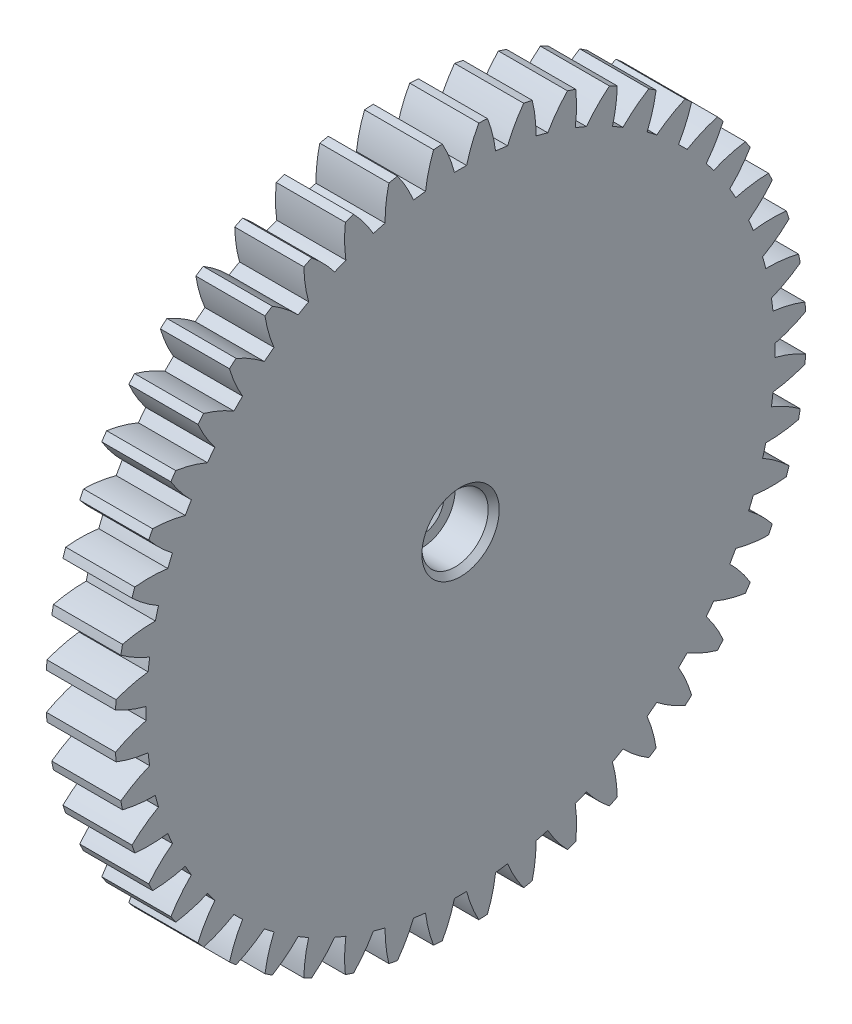
SolidWorks part; units mm, degrees
ref_plane "Plane1" through (0, 0, 0) normal (0, 0, 1) x (1, 0, 0)
ref_plane "Plane2" through (0, 0, 0) normal (0, 1, 0) x (1, 0, 0)
ref_plane "Plane3" through (0, 0, 0) normal (1, 0, 0) x (0, 0, -1)
other "Configuration Table"
sketch "HoldingSke" plane through (0, 0, 0) normal (0, 1, 0) x (1, 0, 0)
  line L0 (0, 0) -> (0.6691, -0.7431)
  line L1 (-15, 0) -> (100, 0) construction
  line L2 (0, 0) -> (-2.1039, 2.3779)
  line L3 (0, 0) -> (-11.863, 4.5341)
  line L4 (0, 0) -> (5.7786, 6.4178)
  line L5 (0, 0) -> (-46.8476, -17.4728)
  line L6 (0, 0) -> (-4.1448, -2.7965)
  line L7 (-2.1039, 2.3779) -> (8.6586, 51.2059)
  line L8 (-76.2, 54.61) -> (-76.1, 54.61)
  line L9 (-71.009, 38.7566) -> (-53.1078, 45.2721)
  line L10 (-76.2, 71.12) -> (104.1128, 71.12)
  line L11 (0, 0) -> (-5, 0)
  line L12 (-76.2, 101.6) -> (-76.162, 101.6)
  line L13 (24.9733, 27.94) -> (52.9518, 28.4284)
  line L14 (24.9733, 27.94) -> (24.9743, 27.94)
  line L15 (24.9733, 27.94) -> (100.4006, 29.5858)
  line L16 (-63.627, -1) -> (-12.827, -1)
  circle A0 centre (0, 0) radius 0.5
  circle A1 centre (0, 0) radius 22.749
  circle A2 centre (0, 0) radius 37.5
  circle A3 centre (0, 0) radius 0.5
  dimension "MHD" = 45.498
  dimension "Hub_dia" = 75
  dimension "Bore" = 1
  dimension "MBD" = 1
  dimension "Num_teeth" = 48
  dimension "Pitch" = 1
  dimension "Overall_len" = 50
  dimension "Show_teeth" = 48
  dimension "Thickness" = 5
  dimension "OAL" = 50.0001
  dimension "T_dim" = 0.1
  dimension "Ap" = 20
  dimension "H" = 19.05
  dimension "Pitch_radius" = 180.3128
  dimension "Width" = 5
  dimension "Backlash" = 0.038
  dimension "Addendum_fac" = 1
  dimension "Dedendum_fac" = 1.25
  dimension "Clearance_fac" = 0.25
  dimension "Dedendum_add" = 0.001
  dimension "Module" = 1
sketch "BasProSke" plane through (0, 0, 0) normal (0, 1, 0) x (1, 0, 0)
  line L0 (-10, 0) -> (60, 0) construction
  line L1 (0, 0) -> (0, 25)
  line L2 (0, 0) -> (5, 0)
  line L3 (5, 0) -> (5, 25)
  line L4 (5, 25) -> (0, 25)
  dimension "Thickness" = 5
  dimension "Diameter" = 50
revolve "Base-Revolve" add sketch "BasProSke" angle 360 about L0
sketch "TooCutSke" plane through (0, 0, 0) normal (1, 0, 0) x (0, 0, -1)
  line L1 (0, 0) -> (0, 107) construction
  line L2 (0, 0) -> (-0.8518, 23.9849) construction
  line L3 (0, 0) -> (-3.1379, 47.8757) construction
  line L4 (-0.8518, 23.9849) -> (-1.569, 23.9379) construction
  arc A0 (0.4395, 22.7448) -> (-0.4395, 22.7448) centre (0, 0) ccw
  arc A1 (1.3336, 24.9898) -> (-1.3336, 24.9898) centre (0, 0) ccw
  circle A2 centre (0, 0) radius 24 construction
  circle A3 centre (0, 0) radius 22.5526 construction
  arc A4 (-0.4395, 22.7448) -> (-1.3336, 24.9898) centre (-9.7344, 20.3436) ccw
  arc A5 (1.3336, 24.9898) -> (0.4395, 22.7448) centre (9.7344, 20.3436) ccw
  dimension "Root_dia" = 45.498
  dimension "Overcut_dia" = 50.0508
  dimension "Pitch_dia" = 48
  dimension "Base_dia" = 45.1052
  dimension "Flank_rad" = 9.6
  dimension "Half_ang" = 3.75
  dimension "Half_CT" = 0.7188
extrude "ToothCut" cut sketch "TooCutSke" along normal through all
fillet "Breaks" [suppressed] radius 0.02
fillet "RootFillets" [suppressed] radius 0.251
pattern_circular "TeethCuts" count 48 every 7.5 about axis through (-10, 0, 0) along (1, 0, 0) of "ToothCut", "RootFillets", "Breaks"
sketch "HubNeaOneSke" plane through (0, 0, 0) normal (-1, 0, 0) x (0, 0, 1)
  circle A0 centre (0, 0) radius 22.749
  dimension "Diameter" = 45.498
extrude "HubNearOne" [suppressed] add sketch "HubNeaOneSke" along normal blind 45.0001
sketch "HubNeaBotSke" plane through (0, 0, 0) normal (-1, 0, 0) x (0, 0, 1)
  circle A0 centre (0, 0) radius 22.749
  dimension "Diameter" = 45.498
extrude "HubNearBoth" [suppressed] add sketch "HubNeaBotSke" along normal blind 22.5
ref_plane "FarPln" through (5, 0, 0) normal (1, 0, 0) x (0, 0, -1)
sketch "HubFarSke" plane through (5, 0, 0) normal (1, 0, 0) x (0, 0, -1)
  circle A0 centre (0, 0) radius 22.749
  dimension "Diameter" = 45.498
extrude "HubFar" [suppressed] add sketch "HubFarSke" along normal blind 22.5
sketch "BorSke" plane through (0, 0, 0) normal (1, 0, 0) x (0, 0, -1)
  circle A0 centre (0, 0) radius 0.5
  dimension "Diameter" = 1
extrude "Bore" cut sketch "BorSke" along normal mid plane 100.0001
sketch "KeySke" plane through (0, 0, 0) normal (1, 0, 0) x (0, 0, -1)
  line L0 (-0.05, 0) -> (-0.05, 0.6)
  line L1 (-0.05, 0.6) -> (0.05, 0.6)
  line L2 (0.05, 0.6) -> (0.05, 0)
  line L3 (0, 0) -> (0, 34) construction
  line L4 (-0.05, 0) -> (0.05, 0)
  dimension "Offset" = 0.6
  dimension "Width" = 0.1
extrude "Keyway" [suppressed] cut sketch "KeySke" along normal mid plane 100.0001
pattern_circular "Keyway2" [suppressed] count 2 every 90 about axis through (-10, 0, 0) along (1, 0, 0)
sketch "草图2" plane through (5, 0, 0) normal (1, 0, 0) x (0, 0, -1)
  circle A0 centre (0, 0) radius 1.2
  dimension "D1" = 2.4
extrude "切除-拉伸1" cut sketch "草图2" against normal through all
sketch "草图3" plane through (5, 0, 0) normal (1, 0, 0) x (0, 0, -1)
  circle A0 centre (0, 0) radius 2.4
  dimension "D1" = 4.8
extrude "切除-拉伸2" cut sketch "草图3" against normal blind 2.8
chamfer "倒角1" distance 0.4 angle 45 3 edges at (2.2, 0, -1.2) (0, 0, -1.2) (5, 0, -2.4)
equation "' \"Module@HoldingSke\" = 6.35"
equation "' \"Num_teeth@HoldingSke\" = 12"
equation "' \"Ap@HoldingSke\" =  20"
equation "' \"Ap@HoldingSke\" = 20"
equation "' \"Width@HoldingSke\" = 0.5 * 25.4"
equation "' \"Hub_dia@HoldingSke\"= 1 * 25.4"
equation "' \"Hub_dia@HoldingSke\" = 1 * 25.4"
equation "' \"Overall_len@HoldingSke\" = 1.0 * 25.4"
equation "' \"Bore@HoldingSke\" = 0.75 * 25.4"
equation "' \"T_dim@HoldingSke\" = 0.1 * 25.4"
equation "' \"Width@KeySke\" = 0.25 * 25.4"
equation "' \"Show_teeth@HoldingSke\" = 13"
equation "' \"Backlash@HoldingSke\" = 0.009 * 25.4"
equation "' \"Addendum_fac@HoldingSke\" = 1.0"
equation "' \"Dedendum_fac@HoldingSke\" = 1.25"
equation "' \"Dedendum_add@HoldingSke\" = 0.00005 * 25.4"
equation "' \"Clearance_fac@HoldingSke\" = 0.25"
equation "\"Pitch@HoldingSke\" = 1 / \"Module@HoldingSke\""
equation "\"Overcut_dia@TooCutSke\" = (\"Num_teeth@HoldingSke\" + 2 * \"Addendum_fac@HoldingSke\") / \"Pitch@HoldingSke\" + 0.002 * 25.4"
equation "\"Pitch_dia@TooCutSke\" = \"Num_teeth@HoldingSke\" / \"Pitch@HoldingSke\""
equation "\"Base_dia@TooCutSke\" = \"Num_teeth@HoldingSke\" / \"Pitch@HoldingSke\" * cos((\"Ap@HoldingSke\"  * 3.14159265 / 180))"
equation "\"Root_dia@TooCutSke\" = (\"Num_teeth@HoldingSke\" + 2) / \"Pitch@HoldingSke\" - 2 * (\"Addendum_fac@HoldingSke\" + \"Dedendum_fac@HoldingSke\") / \"Pitch@HoldingSke\" - \"Dedendum_add@HoldingSke\" * 2"
equation "\"Half_ang@TooCutSke\" = 180 / \"Num_teeth@HoldingSke\""
equation "\"Half_CT@TooCutSke\" = \"Num_teeth@HoldingSke\" / \"Pitch@HoldingSke\" * sin((3.14159265 / 2 / \"Num_teeth@HoldingSke\")) / 2 - 7 * \"Backlash@HoldingSke\" / 4"
equation "\"Flank_rad@TooCutSke\" = \"Num_teeth@HoldingSke\" / \"Pitch@HoldingSke\" / 5"
equation "\"Radius@RootFillets\" = \"Clearance_fac@HoldingSke\" / \"Pitch@HoldingSke\" + \"Dedendum_add@HoldingSke\""
equation "\"Break_rad@Breaks\" = 0.02 / \"Pitch@HoldingSke\""
equation "\"Thickness@HoldingSke\" = \"Width@HoldingSke\""
equation "\"OAL@HoldingSke\" = \"Thickness@HoldingSke\""
equation "\"MHD@HoldingSke\" = (\"Num_teeth@HoldingSke\" + 2) / \"Pitch@HoldingSke\" - 2 * (\"Addendum_fac@HoldingSke\" + \"Dedendum_fac@HoldingSke\")  / \"Pitch@HoldingSke\" - \"Dedendum_add@HoldingSke\" * 2"
equation "\"MBD@HoldingSke\" = (\"Num_teeth@HoldingSke\" + 2) / \"Pitch@HoldingSke\" - 2 * (\"Addendum_fac@HoldingSke\" + \"Dedendum_fac@HoldingSke\")  / \"Pitch@HoldingSke\" - \"Dedendum_add@HoldingSke\" * 2 - 0.002 * 25.4"
equation "\"MHD@HoldingSke\" = ((sgn( \"MHD@HoldingSke\" - \"Hub_dia@HoldingSke\" )-1)*( \"MHD@HoldingSke\" - \"Hub_dia@HoldingSke\" ))/-2+ \"Hub_dia@HoldingSke\""
equation "\"MBD@HoldingSke\" = ((sgn( \"MBD@HoldingSke\" - \"Bore@HoldingSke\" )-1)*( \"MBD@HoldingSke\" - \"Bore@HoldingSke\" ))/-2+ \"Bore@HoldingSke\""
equation "\"OAL@HoldingSke\" = ((sgn( \"OAL@HoldingSke\" - \"Overall_len@HoldingSke\" )+1)*( \"OAL@HoldingSke\" - \"Overall_len@HoldingSke\" ))/2 + \"Overall_len@HoldingSke\" + 0.000002 * 25.4"
equation "\"Num_teeth@TeethCuts\" = int( \"Show_teeth@HoldingSke\" ) + 1"
equation "\"Num_teeth@TeethCuts\" = ((sgn( \"Num_teeth@TeethCuts\" - \"Num_teeth@HoldingSke\" )-1)*( \"Num_teeth@TeethCuts\" - \"Num_teeth@HoldingSke\" ))/-2+ \"Num_teeth@HoldingSke\""
equation "\"Num_teeth@TeethCuts\" = ((sgn( \"Num_teeth@TeethCuts\" - 2.0)+1)*( \"Num_teeth@TeethCuts\" - 2.0))/2 +2.0"
equation "\"Angle@TeethCuts\" = 360.0 / \"Num_teeth@HoldingSke\""
equation "\"Diameter@BasProSke\" = (\"Num_teeth@HoldingSke\" + 2 * \"Addendum_fac@HoldingSke\") / \"Pitch@HoldingSke\""
equation "\"Thickness@BasProSke\"  = \"Thickness@HoldingSke\""
equation "' \"Fillet_rad@BasProSke\" =  \"Thickness@HoldingSke\" * 0.05"
equation "' \"Fillet_rad@BasProSke\" = \"Thickness@HoldingSke\" * 0.05"
equation "\"MHD@HoldingSke\" = ((sgn( \"MHD@HoldingSke\" - \"Root_dia@TooCutSke\" )-1)*( \"MHD@HoldingSke\" - \"Root_dia@TooCutSke\" ))/-2+ \"Root_dia@TooCutSke\""
equation "\"Diameter@HubNeaOneSke\" = \"MHD@HoldingSke\""
equation "\"Length@HubNearOne\" = \"OAL@HoldingSke\" - \"Thickness@BasProSke\""
equation "\"Diameter@HubNeaBotSke\" = \"MHD@HoldingSke\""
equation "\"Length@HubNearBoth\" = ( \"OAL@HoldingSke\" - \"Thickness@BasProSke\" ) / 2.0"
equation "\"Thickness@FarPln\" = \"Thickness@BasProSke\""
equation "\"Diameter@HubFarSke\" = \"MHD@HoldingSke\""
equation "\"Length@HubFar\" = ( \"OAL@HoldingSke\" - \"Thickness@BasProSke\" ) / 2.0"
equation "\"Diameter@BorSke\" = \"MBD@HoldingSke\""
equation "\"D1@Bore\" = \"OAL@HoldingSke\" * 2.0"
equation "\"D1@Keyway\" = \"OAL@HoldingSke\" * 2.0"
equation "\"Offset@KeySke\" = \"T_dim@HoldingSke\" + \"MBD@HoldingSke\" / 2.0"
